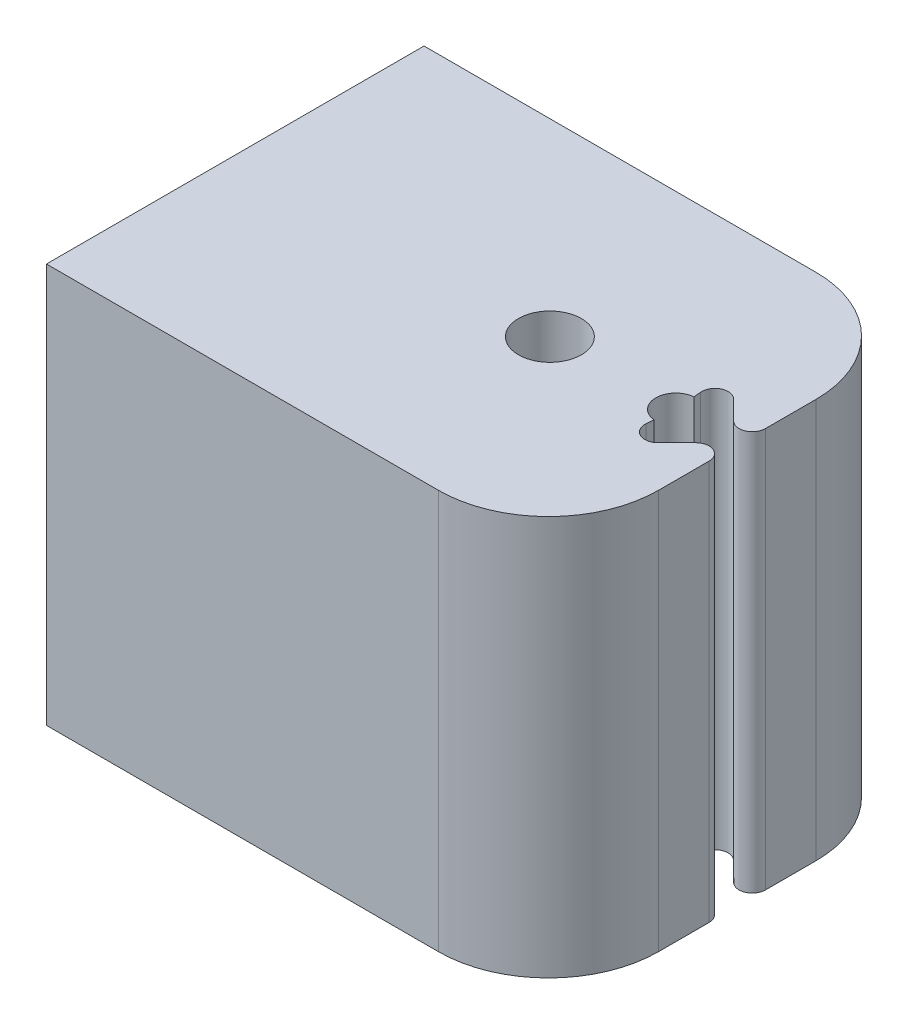
SolidWorks part; units mm, degrees
material "6061 Alloy"
ref_plane "Front Plane" through (0, 0, 0) normal (0, 0, 1) x (1, 0, 0)
ref_plane "Top Plane" through (0, 0, 0) normal (0, 1, 0) x (1, 0, 0)
ref_plane "Right Plane" through (0, 0, 0) normal (1, 0, 0) x (0, 0, -1)
sketch "Sketch1" plane through (0, 0, 0) normal (0, 1, 0) x (1, 0, 0)
  line L0 (0, 0) -> (-4, 0) construction
  line L1 (-4, 0) -> (-4.0553, 0.6326) construction
  line L2 (-4.0553, 0.6326) -> (-4.0758, 0.8669)
  line L3 (-3.3615, 1.2) -> (-2.7615, 0.6)
  line L4 (-4, 0) -> (-3.0808, 0.9192) construction
  line L5 (-6.465, 0.8965) -> (-2.465, 0.8965) construction
  line L6 (-4.0553, -0.6326) -> (-4.0758, -0.8669)
  line L7 (-3.3615, -1.2) -> (-2.7615, -0.6)
  line L8 (-2.0456, 0.8965) -> (-2.0456, 2.5)
  line L12 (-5.5456, 6) -> (-18, 6)
  line L13 (-18, 6) -> (-18, -6)
  line L16 (-2.0456, -0.8965) -> (-2.0456, -2.5)
  line L46 (-18, -6) -> (-5.5456, -6)
  circle A0 centre (-4, 0) radius 0.635 construction
  arc A1 (-4.0758, 0.8669) -> (-3.3615, 1.2) centre (-3.6581, 0.9035) cw
  arc A2 (-2.7615, 0.6) -> (-2.0456, 0.8965) centre (-2.465, 0.8965) ccw
  arc A4 (-4.0553, 0.6326) -> (-4.0553, -0.6326) centre (-4, 0) ccw
  arc A5 (-4.0758, -0.8669) -> (-3.3615, -1.2) centre (-3.6581, -0.9035) ccw
  arc A6 (-2.7615, -0.6) -> (-2.0456, -0.8965) centre (-2.465, -0.8965) cw
  arc A63 (-2.0456, 2.5) -> (-5.5456, 6) centre (-5.5456, 2.5) ccw
  circle A65 centre (-8, 0) radius 1
  arc A86 (-5.5456, -6) -> (-2.0456, -2.5) centre (-5.5456, -2.5) ccw
  point P0 (0, 0)
  dimension "D1" = 1.27
  dimension "D13" = 12
  dimension "D8" = 6
  dimension "D10" = 18
  dimension "D11" = 2
  dimension "D9" = 3.5
  dimension "D2" = 4
  dimension "D3" = 95
  dimension "D4" = 45
  dimension "D5" = 1.2
  dimension "D6" = 1.3
  dimension "D7" = 0.6
  dimension "D12" = 10
extrude "Boss-Extrude1" add sketch "Sketch1" along normal blind 12.7
sketch "Sketch2" plane through (-18, 0, 0) normal (-1, 0, 0) x (0, 0, 1)
  line L0 (-6, 12.7) -> (6, 0) construction
  circle A0 centre (0, 6.35) radius 4
  dimension "D1" = 8
extrude "Cut-Extrude1" cut sketch "Sketch2" against normal blind 10
